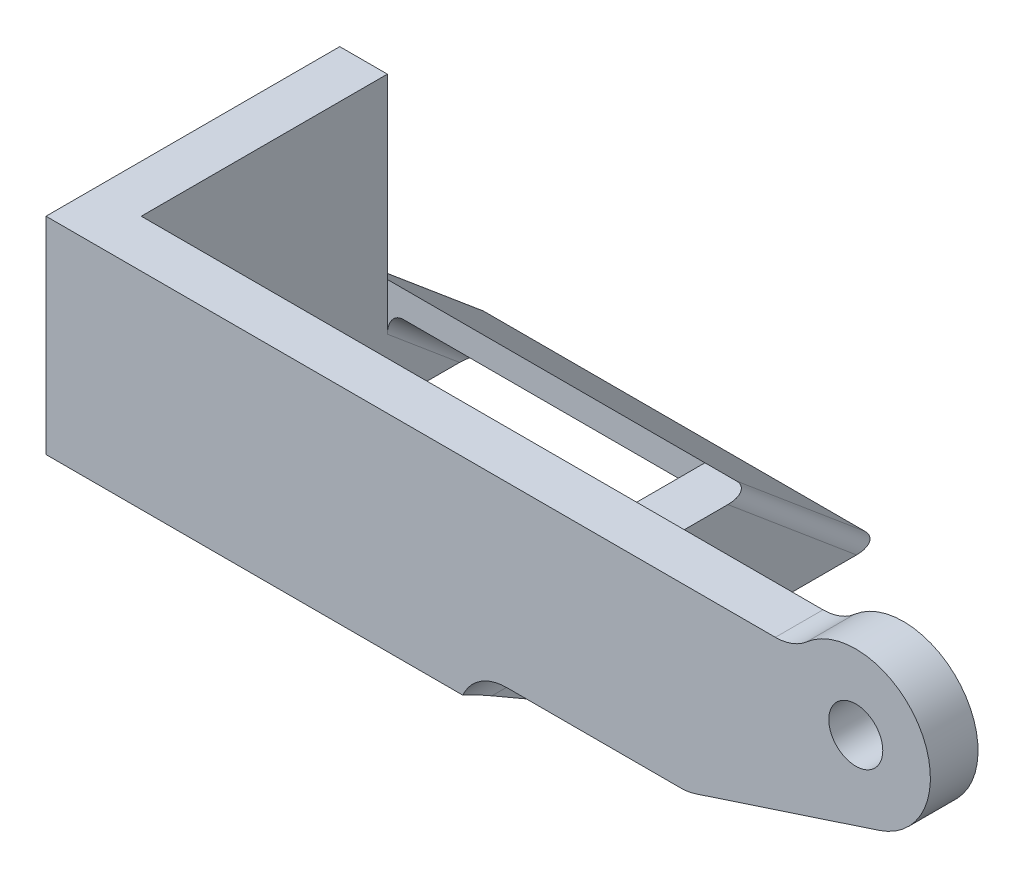
SolidWorks part; units mm, degrees
ref_plane "Front" through (0, 0, 0) normal (0, 0, 1) x (1, 0, 0)
ref_plane "Top" through (0, 0, 0) normal (0, 1, 0) x (1, 0, 0)
ref_plane "Right" through (0, 0, 0) normal (1, 0, 0) x (0, 0, -1)
sketch "Sketch1" plane through (0, 0, 0) normal (0, 0, 1) x (1, 0, 0)
  line L0 (-3.7749, 2.8) -> (-48, 2.8)
  line L1 (-48, 2.8) -> (-48, -10.2)
  line L2 (-48, -10.2) -> (-28, -10.2)
  line L3 (-28, -10.2) -> (-28, -8.4)
  line L4 (-28, -8.4) -> (-10.55, -8.4)
  line L5 (-10.55, -8.4) -> (1.4625, -4.4666)
  circle A0 centre (0, 0) radius 1.7
  arc A1 (-3.7749, 2.8) -> (1.4625, -4.4666) centre (0, 0) cw
  dimension "D1" = 3.4
  dimension "D2" = 3
  dimension "D3" = 20
  dimension "D4" = 48
  dimension "D5" = 2.8
  dimension "D6" = 13
  dimension "D7" = 8.4
extrude "Boss-Extrude1" add sketch "Sketch1" along normal blind 3
sketch "Sketch2" plane through (-48, 0, 0) normal (-1, 0, 0) x (0, 0, 1)
  line L0 (-15.5, 2.8) -> (3, 2.8)
  line L1 (3, 2.8) -> (3, -10.2)
  line L2 (3, -10.2) -> (-5.6603, -15.2)
  line L3 (-5.6603, -15.2) -> (-15.5, -15.2)
  line L4 (-15.5, -15.2) -> (-15.5, 2.8)
  line L5 (3, -10.2) -> (0, -10.2) construction
  line L6 (0, 2.8) -> (0, -10.2) construction
  dimension "D1" = 120
  dimension "D2" = 15.5
  dimension "D3" = 5
extrude "Boss-Extrude2" add sketch "Sketch2" along normal blind 3
sketch "Sketch3" plane through (-48, 0, 0) normal (1, 0, 0) x (0, 0, -1)
  line L0 (-3, -10.2) -> (0, -10.2)
  line L1 (0, -10.2) -> (13.7374, -15.2)
  line L3 (13.7374, -15.2) -> (5.6603, -15.2)
  line L4 (5.6603, -15.2) -> (-3, -10.2)
  line L5 (0, 2.8) -> (0, -10.2) construction
  dimension "D1" = 110
extrude "Boss-Extrude3" add sketch "Sketch3" along normal up to surface (20 mm away) up to face at (-28, -9.3, 1.5)
sketch "Sketch4" plane through (-28, 0, 0) normal (1, 0, 0) x (0, 0, -1)
  line L0 (-3, -10.2) -> (-3, -8.4)
  line L1 (15.5, 2.8) -> (15.5, -15.2) construction
  line L2 (15.5, -8.4) -> (15.5, -15.2)
  line L3 (15.5, -15.2) -> (5.6603, -15.2)
  line L4 (5.6603, -15.2) -> (-3, -10.2)
  line L5 (5.6603, -15.2) -> (-3, -10.2) construction
  line L6 (-3, -10.2) -> (-3, -8.4) construction
  line L7 (-3, -8.4) -> (15.5, -8.4)
extrude "Boss-Extrude4" add sketch "Sketch4" along normal blind 3
fillet "Fillet1" radius 3 3 edges at (-10.55, -8.4, 1.5) (-25, -8.4, 1.5) (-3.7749, 2.8, 1.5)
sketch "Sketch6" plane through (-25, 0, 0) normal (1, 0, 0) x (0, 0, -1)
  line L0 (15.5, -8.4) -> (23.6039, -15.2)
  line L1 (23.6039, -15.2) -> (21.6039, -15.2)
  line L2 (21.6039, -15.2) -> (15.5, -10.0782)
  line L3 (15.5, -15.2) -> (15.5, -8.4) construction
  line L4 (15.5, -10.0782) -> (15.5, -8.4)
  line L5 (5.6603, -15.2) -> (15.5, -15.2) construction
  dimension "D1" = 50
  dimension "D2" = 2
extrude "Boss-Extrude5" add sketch "Sketch6" against normal up to surface (26 mm away) up to face at (-51, -7, -6.1321)
sketch "Sketch7" plane through (-25, 0, 0) normal (1, 0, 0) x (0, 0, -1)
  line L0 (15.5, -15.2) -> (21.6039, -15.2)
  line L1 (21.6039, -15.2) -> (15.5, -10.0782)
  line L2 (15.5, -10.0782) -> (15.5, -15.2)
extrude "Boss-Extrude6" add sketch "Sketch7" against normal up to surface (3 mm away) up to face at (-28, -11.2464, -10.0396)
sketch "Sketch8" plane through (-51, 0, 0) normal (-1, 0, 0) x (0, 0, 1)
  line L0 (-21.6039, -15.2) -> (-15.5, -10.0782)
  line L1 (-15.5, -10.0782) -> (-15.5, -15.2)
  line L2 (-15.5, -15.2) -> (-21.6039, -15.2)
extrude "Boss-Extrude7" add sketch "Sketch8" against normal up to surface (3 mm away) contours L0 L1 L2 up to face at (-48, -6.7112, -9.7125)
fillet "Fillet3" radius 1 7 edges at (-48, -12.7, -6.8687) (-28, -12.7, -6.8687) (-25, -9.9, 0) (-48, -12.6391, -18.552) (-28, -12.6391, -18.552) (-51, -11.8, -19.552) (-25, -11.8, -19.552)
